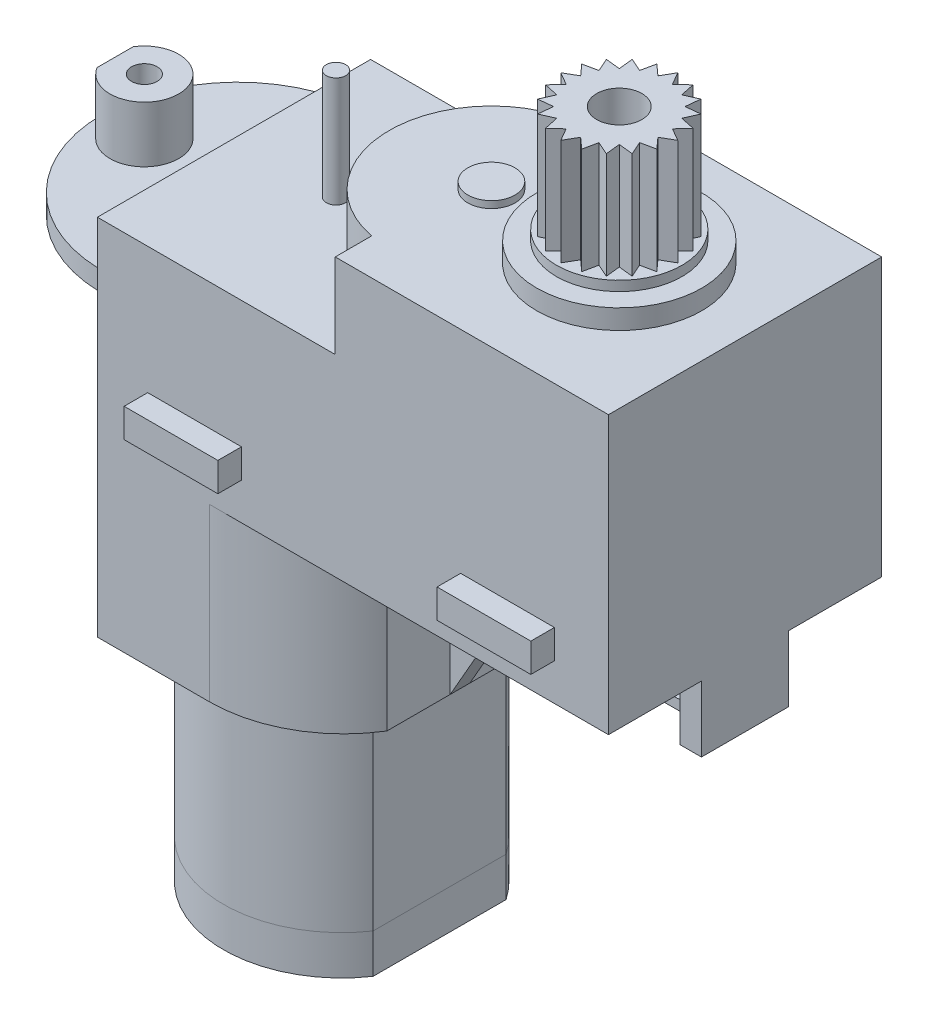
SolidWorks part; units mm, degrees
ref_plane "Front Plane" through (0, 0, 0) normal (0, 0, 1) x (1, 0, 0)
ref_plane "Top Plane" through (0, 0, 0) normal (0, 1, 0) x (1, 0, 0)
ref_plane "Right Plane" through (0, 0, 0) normal (1, 0, 0) x (0, 0, -1)
sketch "Sketch1" plane through (0, 0, 0) normal (0, 1, 0) x (1, 0, 0)
  line L1 (0, -6.95) -> (26, -6.95)
  line L2 (0, -6.95) -> (0, 6.95)
  line L3 (0, 6.95) -> (26, 6.95)
  line L4 (26, -6.95) -> (26, 6.95)
  dimension "D1" = 26
  dimension "D2" = 13.9
extrude "Boss-Extrude1" add sketch "Sketch1" along normal blind 9.8
sketch "Sketch2" plane through (0, 9.8, 0) normal (0, 1, 0) x (1, 0, 0)
  line L0 (26, -6.95) -> (26, 6.95)
  line L1 (26, 6.95) -> (12.1, 6.95)
  line L2 (26, 6.95) -> (0, 6.95) construction
  line L3 (12.1, 6.95) -> (12.1, 5.1)
  line L4 (12.1, -5.1) -> (12.1, -6.95)
  line L5 (0, -6.95) -> (26, -6.95) construction
  line L6 (12.1, -6.95) -> (26, -6.95)
  arc A0 (12.1, 5.1) -> (12.1, -5.1) centre (13.0964, 0) ccw
  point P10 (26, 0)
  point P11 (7.9, 0)
  dimension "D1" = 13.9
  dimension "D2" = 18.1
  dimension "D3" = 10.2
extrude "Boss-Extrude2" add sketch "Sketch2" along normal blind 4.3
sketch "Sketch4" plane through (0, 14.1, 0) normal (0, 1, 0) x (1, 0, 0)
  line L1 (26, -6.95) -> (26, 6.95) construction
  circle A0 centre (19.6, 0) radius 4.2
  point P2 (15.4, 0)
  point P6 (23.8, 0)
  dimension "D1" = 8.4
  dimension "D2" = 2.2
extrude "Boss-Extrude3" add sketch "Sketch4" along normal blind 1
sketch "Sketch5" plane through (0, 15.1, 0) normal (0, 1, 0) x (1, 0, 0)
  circle A0 centre (19.6, 0) radius 3.19
  dimension "D1" = 6.38
extrude "Boss-Extrude4" add sketch "Sketch5" along normal blind 0.5
sketch "Sketch6" plane through (0, 15.6, 0) normal (0, 1, 0) x (1, 0, 0)
  line L0 (19.6, 0) -> (19.6, 2.975) construction
  line L1 (19.6, 0) -> (19.9698, 2.3346) construction
  line L2 (19.6, 0) -> (19.2302, 2.3346) construction
  line L3 (19.2302, 2.3346) -> (19.6, 2.975)
  line L4 (19.6, 2.975) -> (19.9698, 2.3346)
  line L5 (19.9698, 2.3346) -> (20.5193, 2.8294)
  line L6 (20.5193, 2.8294) -> (20.6731, 2.106)
  line L7 (20.6731, 2.106) -> (21.3487, 2.4068)
  line L8 (21.3487, 2.4068) -> (21.2714, 1.6714)
  line L9 (21.2714, 1.6714) -> (22.0068, 1.7487)
  line L10 (22.0068, 1.7487) -> (21.706, 1.0731)
  line L11 (21.706, 1.0731) -> (22.4294, 0.9193)
  line L12 (22.4294, 0.9193) -> (21.9346, 0.3698)
  line L13 (21.9346, 0.3698) -> (22.575, 0)
  line L14 (22.575, 0) -> (21.9346, -0.3698)
  line L15 (21.9346, -0.3698) -> (22.4294, -0.9193)
  line L16 (22.4294, -0.9193) -> (21.706, -1.0731)
  line L17 (21.706, -1.0731) -> (22.0068, -1.7487)
  line L18 (22.0068, -1.7487) -> (21.2714, -1.6714)
  line L19 (21.2714, -1.6714) -> (21.3487, -2.4068)
  line L20 (21.3487, -2.4068) -> (20.6731, -2.106)
  line L21 (20.6731, -2.106) -> (20.5193, -2.8294)
  line L22 (20.5193, -2.8294) -> (19.9698, -2.3346)
  line L23 (19.9698, -2.3346) -> (19.6, -2.975)
  line L24 (19.6, -2.975) -> (19.2302, -2.3346)
  line L25 (19.2302, -2.3346) -> (18.6807, -2.8294)
  line L26 (18.6807, -2.8294) -> (18.5269, -2.106)
  line L27 (18.5269, -2.106) -> (17.8513, -2.4068)
  line L28 (17.8513, -2.4068) -> (17.9286, -1.6714)
  line L29 (17.9286, -1.6714) -> (17.1932, -1.7487)
  line L30 (17.1932, -1.7487) -> (17.494, -1.0731)
  line L31 (17.494, -1.0731) -> (16.7706, -0.9193)
  line L32 (16.7706, -0.9193) -> (17.2654, -0.3698)
  line L33 (17.2654, -0.3698) -> (16.625, 0)
  line L34 (16.625, 0) -> (17.2654, 0.3698)
  line L35 (17.2654, 0.3698) -> (16.7706, 0.9193)
  line L36 (16.7706, 0.9193) -> (17.494, 1.0731)
  line L37 (17.494, 1.0731) -> (17.1932, 1.7487)
  line L38 (17.1932, 1.7487) -> (17.9286, 1.6714)
  line L39 (17.9286, 1.6714) -> (17.8513, 2.4068)
  line L40 (17.8513, 2.4068) -> (18.5269, 2.106)
  line L41 (18.5269, 2.106) -> (18.6807, 2.8294)
  line L42 (18.6807, 2.8294) -> (19.2302, 2.3346)
  circle A0 centre (19.6, 0) radius 1.15
  point P66 (19.6, 0)
  dimension "D1" = 2.3
  dimension "D2" = 18
  dimension "D3" = 9
  dimension "D4" = 2.975
  dimension "D5" = 60
  dimension "D6" = 20
extrude "Boss-Extrude5" add sketch "Sketch6" along normal blind 5.4 contours L42 L41 L40 L39 L38 L37 L36 L35 L34 L33 L32 L31 L30 L29 L28 L27 L26 L25 L24 L23 L22 L21 L20 L19 L18 L17 L16 L15 L14 L13 L12 L11 L10 L9 L8 L7 L6 L5 L4 L3 A0
sketch "Sketch7" plane through (0, 9.8, 0) normal (0, 1, 0) x (1, 0, 0)
  line L0 (26, -6.95) -> (26, 6.95) construction
  circle A0 centre (5.19, 0) radius 0.49
  point P2 (4.7, 0)
  dimension "D1" = 0.98
  dimension "D2" = 21.3
extrude "Boss-Extrude6" add sketch "Sketch7" along normal blind 5.6
sketch "Sketch8" plane through (0, 0, 0) normal (0, -1, 0) x (1, 0, 0)
  line L0 (0, 6.95) -> (26, 6.95) construction
  line L1 (26, -6.95) -> (0, -6.95) construction
  line L6 (13, -6.95) -> (13, 13.6011) construction
  line L7 (11.5, 3.725) -> (11.5, -3.725)
  line L8 (0, 6.95) -> (5.7, 6.95)
  line L9 (0, -6.95) -> (0, 6.95)
  line L10 (5.7, -6.95) -> (0, -6.95)
  arc A2 (5.7, -6.95) -> (11.5, -3.725) centre (5.7, -0.122) ccw
  arc A3 (5.7, 6.95) -> (11.5, 3.725) centre (5.7, 0.122) cw
  point P32 (11.5, 0)
  dimension "D1" = 11.5
  dimension "D2" = 5.7
  dimension "D3" = 7.45
extrude "Boss-Extrude7" add sketch "Sketch8" along normal blind 8.7
sketch "Sketch9" plane through (0, -8.7, 0) normal (0, -1, 0) x (1, 0, 0)
  line L0 (0.5, 3.3823) -> (0.5, -3.3823)
  line L2 (10.46, -3.3823) -> (10.46, 3.3823)
  line L3 (0, 6.95) -> (0, -6.95) construction
  arc A0 (0.5, -3.3823) -> (10.46, -3.3823) centre (5.48, 0) ccw
  arc A1 (10.46, 3.3823) -> (0.5, 3.3823) centre (5.48, 0) ccw
  dimension "D1" = 12.04
  dimension "D2" = 9.96
  dimension "D3" = 0.5
extrude "Boss-Extrude8" add sketch "Sketch9" along normal blind 11.5
sketch "Sketch10" plane through (0, 0, 0) normal (0, -1, 0) x (1, 0, 0)
  line L0 (26, 2.22) -> (26, -2.22)
  line L1 (26, 6.95) -> (26, -6.95) construction
  line L2 (26, -2.22) -> (24.91, -2.22)
  line L3 (24.91, -2.22) -> (24.91, -0.75)
  line L4 (24.91, -0.75) -> (21.49, -0.75)
  line L5 (21.49, -0.75) -> (21.49, -2.22)
  line L6 (21.49, -2.22) -> (20.4, -2.22)
  line L7 (20.4, -2.22) -> (20.4, 2.22)
  line L8 (20.4, 2.22) -> (21.49, 2.22)
  line L9 (21.49, 2.22) -> (21.49, 0.75)
  line L10 (21.49, 0.75) -> (24.91, 0.75)
  line L11 (24.91, 0.75) -> (24.91, 2.22)
  line L12 (24.91, 2.22) -> (26, 2.22)
  point P13 (26, 0)
  dimension "D1" = 5.6
  dimension "D2" = 4.44
  dimension "D3" = 1.5
  dimension "D4" = 3.42
extrude "Boss-Extrude9" add sketch "Sketch10" along normal blind 3.35
sketch "Sketch11" plane through (0, 0, -0.75) normal (0, 0, -1) x (-1, 0, 0)
  line L0 (-24.2, 0) -> (-24.2, -1.85)
  line L1 (-21.49, 0) -> (-24.91, 0) construction
  line L2 (-22.2, -1.85) -> (-22.2, 0)
  line L3 (-26, 0) -> (-5.7, 0) construction
  line L4 (-22.2, 0) -> (-24.2, 0)
  line L5 (-21.49, -3.35) -> (-24.91, -3.35) construction
  arc A0 (-24.2, -1.85) -> (-22.2, -1.85) centre (-23.2, -1.85) ccw
  point P6 (-23.2, -3.35)
  point P10 (-23.2, -2.85)
  dimension "D1" = 2
  dimension "D2" = 0.5
extrude "Cut-Extrude1" cut sketch "Sketch11" against normal through all
sketch "Sketch12" plane through (0, 9.8, 0) normal (0, 1, 0) x (1, 0, 0)
  line L0 (0, 6.95) -> (0, -6.95) construction
  line L1 (0, 6.8768) -> (0, -6.8768)
  arc A0 (0, 6.8768) -> (0, -6.8768) centre (0.1791, 0) ccw
  point P5 (-6.7, 0)
  dimension "D1" = 6.7
extrude "Boss-Extrude10" add sketch "Sketch12" against normal blind 1 from offset 2.3 offset against normal yes
sketch "Sketch13" plane through (0, 7.5, 0) normal (0, 1, 0) x (1, 0, 0)
  line L0 (-6.05, 0.9178) -> (-6.05, -0.9178)
  line L1 (26, -6.95) -> (26, 6.95) construction
  arc A0 (-6.05, -0.9178) -> (-6.05, 0.9178) centre (-4.56, 0) ccw
  point P1 (-2.81, 0)
  dimension "D1" = 1.75
  dimension "D2" = 3.24
  dimension "D3" = 32.05
extrude "Boss-Extrude11" add sketch "Sketch13" along normal blind 2.85
sketch "Sketch15" plane through (0, 10.35, 0) normal (0, 1, 0) x (1, 0, 0)
  circle A0 centre (-4.56, 0) radius 0.65
  dimension "D1" = 1.3
extrude "Cut-Extrude2" cut sketch "Sketch15" against normal through all
sketch "Sketch14" plane through (0, 6.5, 0) normal (0, -1, 0) x (1, 0, 0)
  circle A0 centre (-4.56, 0) radius 1.665
  circle A1 centre (-4.56, 0) radius 0.65
  dimension "D1" = 3.33
extrude "Boss-Extrude12" add sketch "Sketch14" along normal blind 1.8
sketch "Sketch16" plane through (0, 0, 0) normal (0, 0, 1) x (1, 0, 0)
  line L0 (-3.2, 6.5) -> (-3.2, 4.7)
  line L1 (-6.225, 6.5) -> (-2.895, 6.5) construction
  line L2 (-6.225, 4.7) -> (-2.895, 4.7) construction
  line L3 (-1.1787, 2.0658) -> (0, 1.75)
  line L4 (0, 9.8) -> (0, -8.7) construction
  line L5 (0, 1.75) -> (0, 6.5)
  line L6 (0, 6.5) -> (-0.625, 6.5)
  line L7 (0, 7.5) -> (-6.7, 7.5) construction
  line L8 (-2.575, 6.5) -> (-2.575, 4.5)
  line L9 (-0.625, 4.5) -> (-0.625, 6.5)
  line L10 (-2.575, 6.5) -> (-3.2, 6.5)
  line L11 (-6.7, 6.5) -> (0, 6.5) construction
  arc A0 (-3.2, 4.7) -> (-1.1787, 2.0658) centre (-0.4729, 4.7) ccw
  arc A1 (-2.575, 4.5) -> (-0.625, 4.5) centre (-1.6, 4.5) ccw
  dimension "D1" = 5.75
  dimension "D2" = 3.2
  dimension "D3" = 75
  dimension "D4" = 1.95
  dimension "D5" = 2
extrude "Boss-Extrude13" add sketch "Sketch16" along normal mid plane 1.36
ref_plane "Plane1" through (0, -18.2, 0) normal (0, -1, 0) x (-1, 0, 0)
split line "Split Line1"
sketch "Sketch17" plane through (0, 0, 0) normal (0, 0, 1) x (1, 0, 0)
  line L0 (11.5, -8.7) -> (15.9, -1)
  line L1 (15.9, -1) -> (20.4, -1)
  line L2 (20.4, -3.35) -> (20.4, 0) construction
  line L3 (20.4, -1) -> (20.4, 0)
  line L4 (20.4, 0) -> (11.5, 0)
  line L5 (11.5, 0) -> (11.5, -8.7)
  dimension "D1" = 4.5
  dimension "D2" = 1
extrude "Boss-Extrude14" add sketch "Sketch17" along normal mid plane 1
sketch "Sketch18" plane through (0, 14.1, 0) normal (0, 1, 0) x (1, 0, 0)
  circle A0 centre (13.0964, 0) radius 1.2
  arc A1 (12.1, 5.1) -> (12.1, -5.1) centre (13.0964, 0) ccw construction
  dimension "D1" = 2.4
extrude "Boss-Extrude15" add sketch "Sketch18" along normal blind 0.35
sketch "Sketch20" plane through (0, 0, 0) normal (0, 0, 1) x (1, 0, 0)
  line L0 (26, 14.1) -> (26, 0) construction
  line L1 (2.56, 3.35) -> (7.33, 3.35)
  line L2 (2.56, 3.35) -> (2.56, 1.88)
  line L3 (2.56, 1.88) -> (7.33, 1.88)
  line L4 (7.33, 3.35) -> (7.33, 1.88)
  line L5 (18.48, 1.88) -> (23.25, 1.88)
  line L6 (18.48, 1.88) -> (18.48, 3.35)
  line L7 (18.48, 3.35) -> (23.25, 3.35)
  line L8 (23.25, 1.88) -> (23.25, 3.35)
  line L9 (12.1, 14.1) -> (26, 14.1) construction
  line L10 (0, 9.8) -> (0, -8.7) construction
  dimension "D1" = 4.77
  dimension "D2" = 1.47
  dimension "D3" = 2.75
  dimension "D4" = 2.56
  dimension "D5" = 10.75
extrude "Boss-Extrude16" add sketch "Sketch20" along normal mid plane 16.3
sketch "Sketch21" plane through (0, 0, 0) normal (0, -1, 0) x (1, 0, 0)
  line L0 (26, -2.22) -> (26, 2.22) construction
  circle A0 centre (19.7, 0) radius 1.4
  dimension "D1" = 2.8
  dimension "D2" = 6.3
extrude "Boss-Extrude17" add sketch "Sketch21" along normal up to surface (1 mm away) up to face at (18.15, -1, 0)
sketch "Sketch22" plane through (0, -1, 0) normal (0, -1, 0) x (1, 0, 0)
  circle A0 centre (12, 0) radius 1.4
  dimension "D1" = 2.8
  dimension "D2" = 12
extrude "Boss-Extrude18" add sketch "Sketch22" along normal blind 0.5 and the other way up to surface
